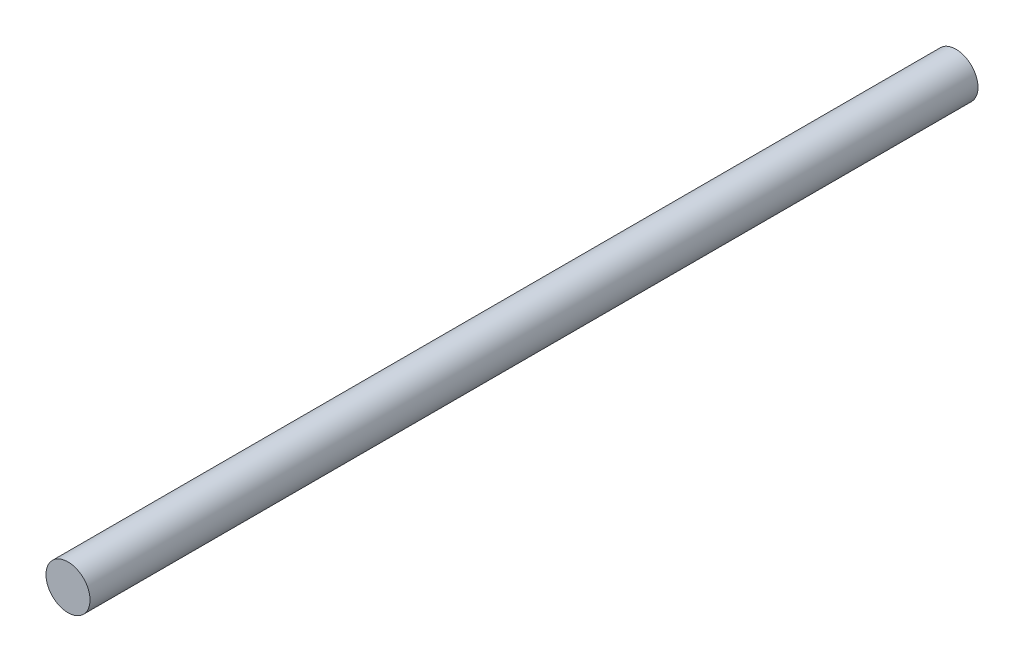
SolidWorks part; units mm, degrees
ref_plane "Front Plane" through (0, 0, 0) normal (0, 0, 1) x (1, 0, 0)
ref_plane "Top Plane" through (0, 0, 0) normal (0, 1, 0) x (1, 0, 0)
ref_plane "Right Plane" through (0, 0, 0) normal (1, 0, 0) x (0, 0, -1)
sketch "Sketch2" plane through (0, 0, 0) normal (0, 0, 1) x (1, 0, 0)
  circle A0 centre (0, 0) radius 1.985
  dimension "D1" = 3.97
extrude "Boss-Extrude1" add sketch "Sketch2" along normal blind 80
